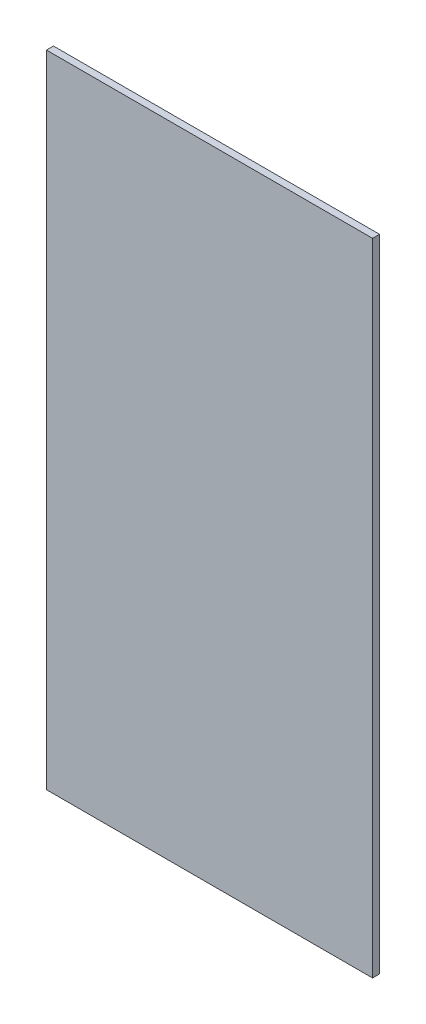
SolidWorks part; units mm, degrees
material "ASTM A36 Steel"
ref_plane "Front Plane" through (0, 0, 0) normal (0, 0, 1) x (1, 0, 0)
ref_plane "Top Plane" through (0, 0, 0) normal (0, 1, 0) x (1, 0, 0)
ref_plane "Right Plane" through (0, 0, 0) normal (1, 0, 0) x (0, 0, -1)
sketch "Sketch1" plane through (0, 0, 0) normal (0, 0, 1) x (1, 0, 0)
  line L1 (-70, -137.5) -> (70, -137.5)
  line L2 (-70, -137.5) -> (-70, 137.5)
  line L3 (-70, 137.5) -> (70, 137.5)
  line L4 (70, -137.5) -> (70, 137.5)
  line L5 (-70, -137.5) -> (70, 137.5) construction
  line L6 (-70, 137.5) -> (70, -137.5) construction
  point P0 (0, 0)
  dimension "D1" = 275
  dimension "D2" = 140
extrude "Boss-Extrude1" add sketch "Sketch1" along normal blind 3
